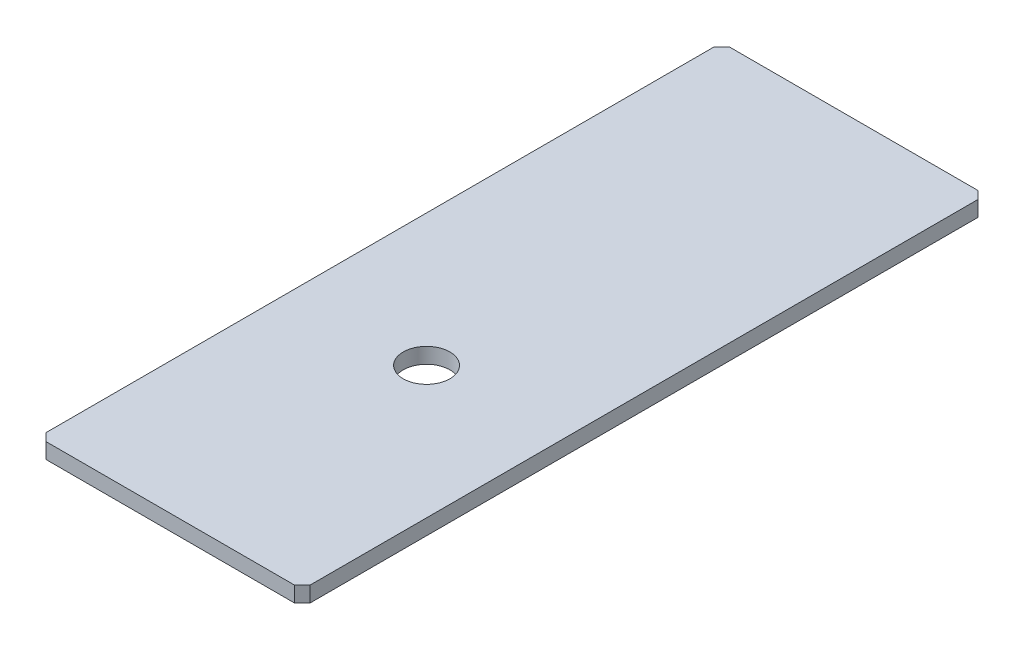
SolidWorks part; units mm, degrees
ref_plane "Alzado" through (0, 0, 0) normal (0, 0, 1) x (1, 0, 0)
ref_plane "Planta" through (0, 0, 0) normal (0, 1, 0) x (1, 0, 0)
ref_plane "Vista lateral" through (0, 0, 0) normal (1, 0, 0) x (0, 0, -1)
sketch "Croquis1" plane through (0, 0, 0) normal (0, 1, 0) x (1, 0, 0)
  line L0 (8, 22) -> (8.5, 21.5)
  line L1 (-8, 22) -> (8, 22)
  line L2 (-8.5, 21.5) -> (-8.5, -21.5)
  line L3 (-8, -22) -> (8, -22)
  line L4 (8.5, 21.5) -> (8.5, -21.5)
  line L5 (-8.5, 22) -> (8.5, -22) construction
  line L6 (-8.5, -22) -> (8.5, 22) construction
  line L7 (-8.5, 21.5) -> (-8, 22)
  line L8 (-8.5, -21.5) -> (-8, -22)
  line L9 (8, -22) -> (8.5, -21.5)
  circle A0 centre (0, -5.5) radius 1.5
  point P0 (0, 0)
  dimension "D3" = 3
  dimension "D1" = 44
  dimension "D2" = 17
  dimension "D4" = 16.5
extrude "Saliente-Extruir1" add sketch "Croquis1" along normal blind 1
